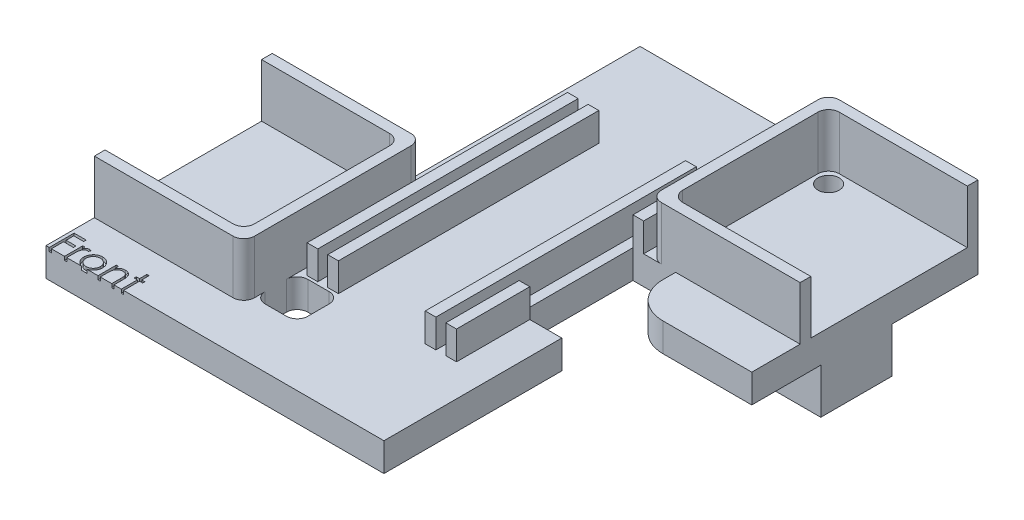
SolidWorks part; units mm, degrees
ref_plane "Front Plane" through (0, 0, 0) normal (0, 0, 1) x (1, 0, 0)
ref_plane "Top Plane" through (0, 0, 0) normal (0, 1, 0) x (1, 0, 0)
ref_plane "Right Plane" through (0, 0, 0) normal (1, 0, 0) x (0, 0, -1)
sketch "Sketch1" plane through (0, 0, 0) normal (0, 1, 0) x (1, 0, 0)
  line L1 (-15, 33) -> (32.5, 33)
  line L2 (-32.5, -1.2) -> (-32.5, -33)
  line L3 (-32.5, -33) -> (15, -33)
  line L4 (32.5, 33) -> (32.5, 1.2)
  line L5 (-15, 15.2308) -> (15, -15.2308) construction
  line L6 (-32.5, -33) -> (32.5, 33) construction
  line L9 (32.5, 1.2) -> (15, 1.2)
  line L10 (15, -33) -> (15, 1.2)
  line L13 (-32.5, -1.2) -> (-15, -1.2)
  line L14 (-15, 33) -> (-15, -1.2)
  point P0 (0, 0)
  dimension "D3" = 17.5
  dimension "D4" = 17.5
  dimension "D5" = 34.2
  dimension "D6" = 34.2
extrude "Boss-Extrude1" add sketch "Sketch1" along normal blind 4
sketch "Sketch2" plane through (0, 4, 0) normal (0, 1, 0) x (1, 0, 0)
  line L0 (32.5, 31.5) -> (14.5, 31.5)
  line L1 (32.5, 33) -> (13, 33)
  line L2 (32.5, 33) -> (32.5, 31.5)
  line L3 (32.5, 8) -> (13, 8)
  line L4 (11.5, 31.5) -> (11.5, 9.5)
  line L5 (13, 30) -> (13, 11)
  line L6 (14.5, 9.5) -> (32.5, 9.5)
  line L7 (32.5, 9.5) -> (32.5, 8)
  line L8 (0, 0) -> (-10.8209, 0) construction
  line L9 (-10.8209, 0) -> (0, 0) construction
  line L10 (0, 0) -> (0, -9.9611) construction
  arc A0 (13, 8) -> (11.5, 9.5) centre (13, 9.5) cw
  arc A1 (13, 11) -> (14.5, 9.5) centre (14.5, 11) ccw
  arc A2 (13, 33) -> (11.5, 31.5) centre (13, 31.5) ccw
  arc A3 (14.5, 31.5) -> (13, 30) centre (14.5, 30) ccw
  dimension "D6" = 1.5
  dimension "D1" = 21
  dimension "D2" = 25
  dimension "D3" = 1.5
  dimension "D4" = 1.5
  dimension "D5" = 1.5
extrude "Boss-Extrude2" add sketch "Sketch2" along normal blind 7.5
sketch "Sketch3" plane through (0, 4, 0) normal (0, 1, 0) x (1, 0, 0)
  line L0 (11.5, 29.5) -> (15, 29.5) construction
  line L1 (11.5, 31.5) -> (11.5, 9.5) construction
  line L2 (15, 29.5) -> (15, 33) construction
  line L3 (32.5, 33) -> (13, 33) construction
  dimension "D1" = 3.5
  dimension "D2" = 3.5
sketch "Sketch5" plane through (0, 4, 0) normal (0, 1, 0) x (1, 0, 0)
  line L0 (-32.5, -2.7) -> (-14.5, -2.7)
  line L1 (-32.5, -1.2) -> (-13, -1.2)
  line L2 (-32.5, -1.2) -> (-32.5, -2.7)
  line L3 (-32.5, -26.2) -> (-13, -26.2)
  line L4 (-11.5, -2.7) -> (-11.5, -24.7)
  line L5 (-13, -4.2) -> (-13, -23.2)
  line L6 (-14.5, -24.7) -> (-32.5, -24.7)
  line L7 (-32.5, -24.7) -> (-32.5, -26.2)
  arc A0 (-13, -1.2) -> (-11.5, -2.7) centre (-13, -2.7) cw
  arc A1 (-13, -26.2) -> (-11.5, -24.7) centre (-13, -24.7) ccw
  arc A2 (-13, -23.2) -> (-14.5, -24.7) centre (-14.5, -23.2) cw
  arc A3 (-14.5, -2.7) -> (-13, -4.2) centre (-14.5, -4.2) cw
  dimension "D6" = 1.5
  dimension "D1" = 21
  dimension "D2" = 25
  dimension "D3" = 1.5
  dimension "D4" = 1.5
  dimension "D5" = 1.5
extrude "Boss-Extrude3" add sketch "Sketch5" along normal blind 7.5
sketch "Sketch6" plane through (0, 4, 0) normal (0, 1, 0) x (1, 0, 0)
  line L0 (-15, -26.2) -> (-15, -22.7) construction
  line L1 (-32.5, -26.2) -> (-13, -26.2) construction
  line L2 (-15, -22.7) -> (-11.5, -22.7) construction
  line L3 (-11.5, -24.7) -> (-11.5, -2.7) construction
  circle A0 centre (-15, -22.7) radius 1.5
  circle A1 centre (15, 29.5) radius 1.5
  dimension "D3" = 3
  dimension "D4" = 3
  dimension "D1" = 3.5
  dimension "D2" = 3.5
extrude "Cut-Extrude1" cut sketch "Sketch6" against normal through all
sketch "Sketch7" plane through (0, 4, 0) normal (0, 1, 0) x (1, 0, 0)
  line L0 (0, 0) -> (0, 34.4926) construction
  line L1 (0, 0) -> (-9, 0) construction
  line L2 (-9, -18.3) -> (-9, 18.3)
  line L3 (-9, 18.3) -> (-10.5, 18.3)
  line L4 (-10.5, 18.3) -> (-10.5, -18.3)
  line L6 (-9, -18.3) -> (-10.5, -18.3)
  line L7 (-9, 2.8922) -> (-8.3, 2.8922) construction
  line L8 (-8.3, 2.8922) -> (-8.3, 1.7687) construction
  line L9 (-7.6, 18.3) -> (-6.1, 18.3)
  line L10 (-7.6, -18.3) -> (-7.6, 18.3)
  line L11 (-7.6, -18.3) -> (-6.1, -18.3)
  line L12 (-6.1, 18.3) -> (-6.1, -18.3)
  line L13 (7.6, -18.3) -> (7.6, 18.3)
  line L14 (7.6, -18.3) -> (6.1, -18.3)
  line L15 (6.1, 18.3) -> (6.1, -18.3)
  line L16 (7.6, 18.3) -> (6.1, 18.3)
  line L17 (9, 18.3) -> (10.5, 18.3)
  line L18 (9, -18.3) -> (9, 18.3)
  line L19 (9, -18.3) -> (10.5, -18.3)
  line L20 (10.5, 18.3) -> (10.5, -18.3)
  dimension "D1" = 9
  dimension "D2" = 18.3
  dimension "D3" = 1.5
  dimension "D4" = 0.7
extrude "Boss-Extrude4" add sketch "Sketch7" along normal blind 4
sketch "Sketch8" plane through (0, 8, 0) normal (0, 1, 0) x (1, 0, 0)
  line L0 (0, 0) -> (9, 0) construction
  line L1 (9, 18.3) -> (9, -18.3) construction
  line L3 (9, -8) -> (9, 8)
  line L4 (9, 8) -> (15, 8)
  line L5 (15, -8) -> (15, 8)
  line L6 (13, 8) -> (32.5, 8) construction
  line L7 (9, -8) -> (15, -8)
  line L8 (15, 0) -> (26.2252, 0) construction
  dimension "D1" = 6
extrude "Cut-Extrude2" cut sketch "Sketch8" against normal through all
sketch "Sketch10" plane through (32.5, 0, 0) normal (1, 0, 0) x (0, 0, -1)
  line L0 (20.5, 0) -> (20.5, -4.95) construction
  line L1 (1.2, 0) -> (33, 0) construction
  line L2 (20.5, -4.95) -> (20.5, -6.35) construction
  dimension "D1" = 4.95
  dimension "D2" = 1.4
sketch "Sketch12" plane through (0, 0, 0) normal (0, -1, 0) x (1, 0, 0)
  line L0 (32.5, -33) -> (32.5, -15.9) construction
  line L1 (32.5, -1.2) -> (32.5, -33) construction
  line L2 (32.5, -10.9) -> (22.5, -10.9)
  line L4 (32.5, -10.9) -> (32.5, -20.9)
  line L5 (32.5, -20.9) -> (22.5, -20.9)
  line L6 (22.5, -10.9) -> (22.5, -20.9)
  line L7 (-32.5, 1.2) -> (-32.5, 18.3) construction
  line L8 (-32.5, 1.2) -> (-32.5, 33) construction
  line L10 (-32.5, 23.3) -> (-22.5, 23.3)
  line L12 (-32.5, 23.3) -> (-32.5, 13.3)
  line L13 (-32.5, 13.3) -> (-22.5, 13.3)
  line L14 (-22.5, 23.3) -> (-22.5, 13.3)
  dimension "D1" = 17.1
  dimension "D2" = 17.1
  dimension "D3" = 10
  dimension "D4" = 10
  dimension "D5" = 10
extrude "Boss-Extrude5" add sketch "Sketch12" along normal blind 6.35
sketch "Sketch14" plane through (0, 4, 0) normal (0, 1, 0) x (1, 0, 0)
  line L0 (-11.5, -24.7) -> (-11.5, -2.7) construction
  line L1 (-10, -18.7) -> (-7, -18.7)
  line L2 (-11.5, -20.2) -> (-11.5, -23.2)
  line L3 (-10, -24.7) -> (-7, -24.7)
  line L4 (-5.5, -20.2) -> (-5.5, -23.2)
  line L5 (-7.6, -18.3) -> (-6.1, -18.3) construction
  line L6 (11.5, 31.5) -> (11.5, 9.5) construction
  line L7 (10, 18.7) -> (7, 18.7)
  line L8 (11.5, 20.2) -> (11.5, 23.2)
  line L9 (10, 24.7) -> (7, 24.7)
  line L10 (5.5, 20.2) -> (5.5, 23.2)
  line L11 (7.6, 18.3) -> (6.1, 18.3) construction
  arc A0 (-7, -24.7) -> (-5.5, -23.2) centre (-7, -23.2) ccw
  arc A1 (-11.5, -23.2) -> (-10, -24.7) centre (-10, -23.2) ccw
  arc A2 (-10, -18.7) -> (-11.5, -20.2) centre (-10, -20.2) ccw
  arc A3 (-7, -18.7) -> (-5.5, -20.2) centre (-7, -20.2) cw
  arc A4 (7, 18.7) -> (5.5, 20.2) centre (7, 20.2) cw
  arc A5 (10, 18.7) -> (11.5, 20.2) centre (10, 20.2) ccw
  arc A6 (11.5, 23.2) -> (10, 24.7) centre (10, 23.2) ccw
  arc A7 (7, 24.7) -> (5.5, 23.2) centre (7, 23.2) ccw
  point P12 (-11.5, -18.7)
  point P27 (5.5, 18.7)
  point P30 (11.5, 18.7)
  point P33 (11.5, 24.7)
  point P36 (5.5, 24.7)
  dimension "D3" = 1.5
  dimension "D8" = 1.5
  dimension "D1" = 6
  dimension "D2" = 6
  dimension "D4" = 0.4
  dimension "D5" = 0.4
  dimension "D6" = 6
  dimension "D7" = 6
extrude "Cut-Extrude3" cut sketch "Sketch14" against normal through all
sketch "Sketch16" plane through (0, 4, 0) normal (0, 1, 0) x (1, 0, 0)
  line L0 (-32.5, -33) -> (-11.1838, -33) construction
  line L1 (-32.5, -33) -> (15, -33) construction
  text T0 "Front"
extrude "Cut-Extrude4" cut sketch "Sketch16" against normal blind 0.5
fillet "Fillet1" radius 5 1 edges at (15, 2, -1.2)
